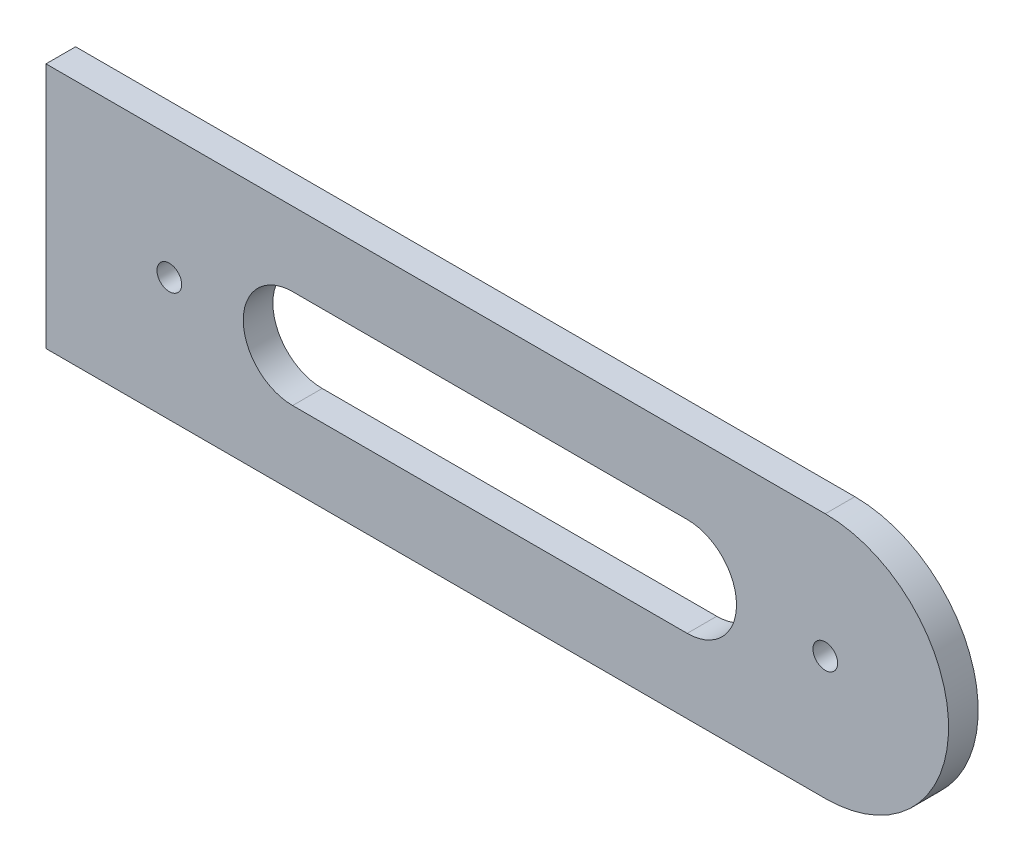
SolidWorks part; units mm, degrees
material "Teak"
ref_plane "Front Plane" through (0, 0, 0) normal (0, 0, 1) x (1, 0, 0)
ref_plane "Top Plane" through (0, 0, 0) normal (0, 1, 0) x (1, 0, 0)
ref_plane "Right Plane" through (0, 0, 0) normal (1, 0, 0) x (0, 0, -1)
sketch "Sketch1" plane through (0, 0, 0) normal (0, 0, 1) x (1, 0, 0)
  point P0 (0, 0)
  line B0 (0, -50) -> (158, -50)
  line B1 (158, 0) -> (0, 0)
  line B2 (0, 0) -> (0, -50)
  line B3 (50, -35) -> (130, -35)
  line B4 (130, -15) -> (50, -15)
  arc B5 (158, -50) -> (158, 0) centre (158, -25) ccw
  circle B6 centre (25, -25) radius 2.5
  circle B7 centre (158, -25) radius 2.5
  arc B8 (130, -35) -> (130, -15) centre (130, -25) ccw
  arc B9 (50, -15) -> (50, -35) centre (50, -25) ccw
sketch_block_instance "Block1-1"
sketch_block "Block1"
extrude "Boss-Extrude1" add sketch "Sketch1" along normal blind 6
